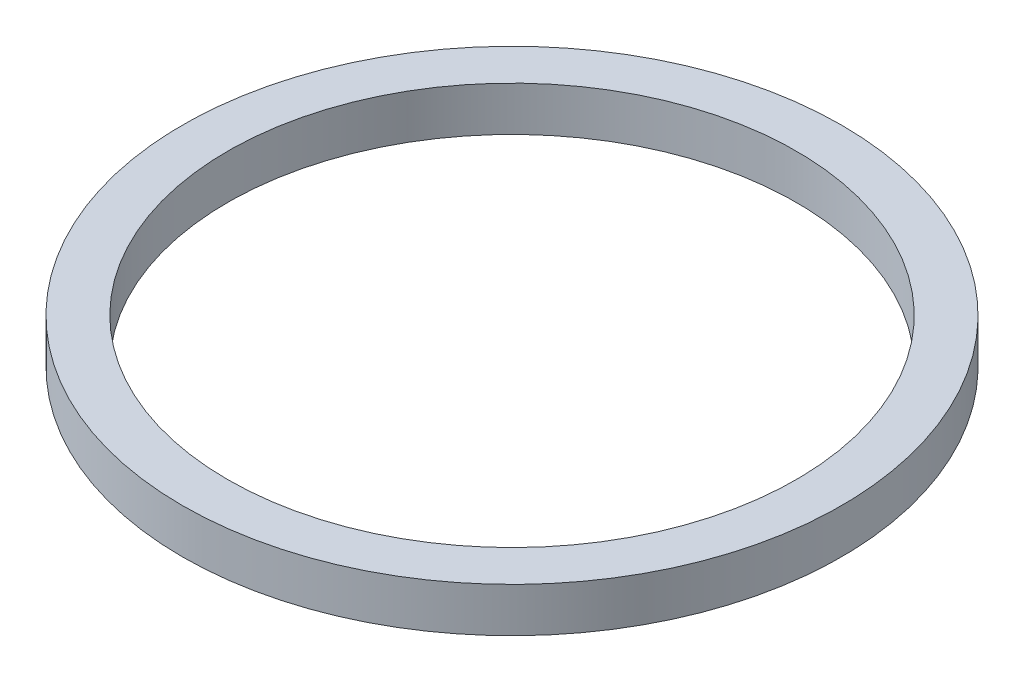
SolidWorks part; units mm, degrees
ref_plane "Front Plane" through (0, 0, 0) normal (0, 0, 1) x (1, 0, 0)
ref_plane "Top Plane" through (0, 0, 0) normal (0, 1, 0) x (1, 0, 0)
ref_plane "Right Plane" through (0, 0, 0) normal (1, 0, 0) x (0, 0, -1)
sketch "Sketch2" plane through (0, 0, 0) normal (0, 1, 0) x (1, 0, 0)
  circle A0 centre (0, 0) radius 160
  circle A1 centre (0, 0) radius 185.4
  dimension "D1" = 320
  dimension "D2" = 25.4
extrude "Boss-Extrude1" add sketch "Sketch2" along normal blind 25
